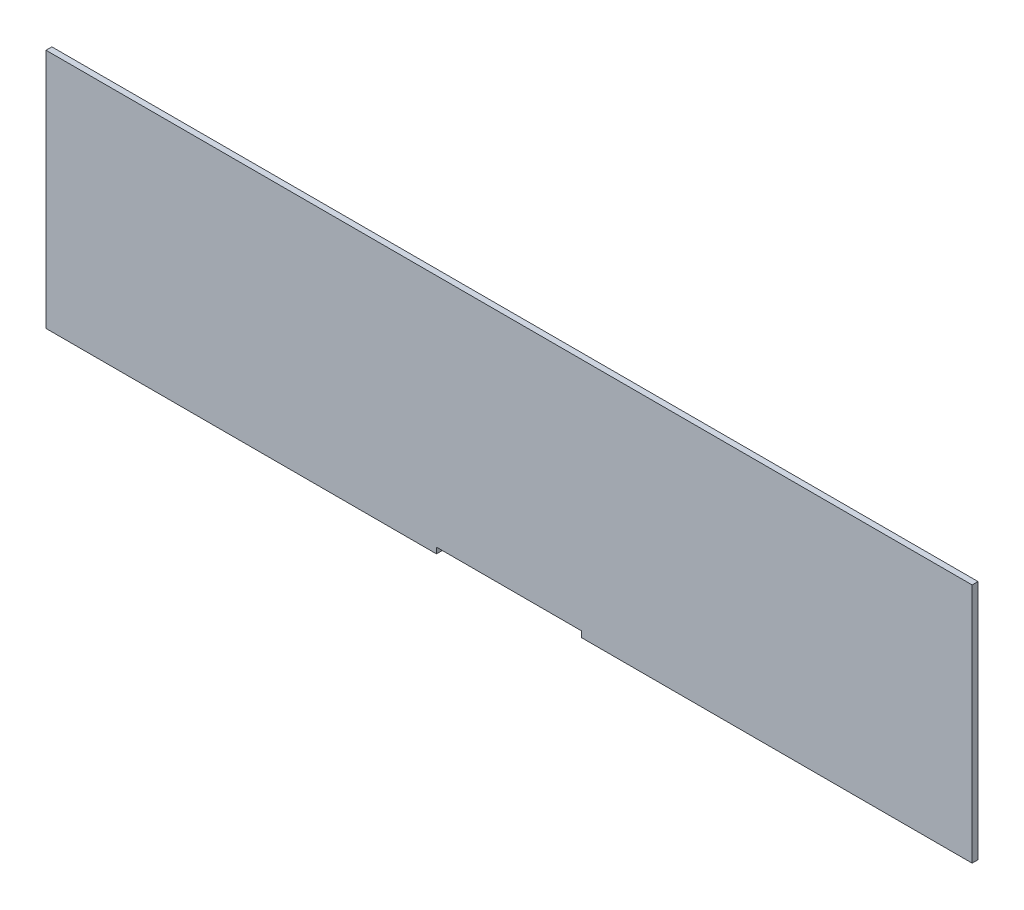
SolidWorks part; units mm, degrees
ref_plane "Front Plane" through (0, 0, 0) normal (0, 0, 1) x (1, 0, 0)
ref_plane "Top Plane" through (0, 0, 0) normal (0, 1, 0) x (1, 0, 0)
ref_plane "Right Plane" through (0, 0, 0) normal (1, 0, 0) x (0, 0, -1)
sketch "Sketch1" plane through (0, 0, 0) normal (0, 0, 1) x (1, 0, 0)
  line L0 (-37.055, 3) -> (37.055, 3)
  line L1 (-236.355, 123) -> (236.355, 123)
  line L2 (-236.355, 123) -> (-236.355, 0)
  line L3 (-236.355, 0) -> (-37.055, 0)
  line L4 (236.355, 123) -> (236.355, 0)
  line L5 (-37.055, 3) -> (-37.055, 0)
  line L6 (0, 3) -> (0, 0) construction
  line L7 (37.055, 3) -> (37.055, 0)
  line L8 (37.055, 0) -> (236.355, 0)
  point P10 (0, 0)
  dimension "D1" = 472.71
  dimension "D2" = 123
  dimension "D3" = 74.11
  dimension "D4" = 3
  dimension "D5" = 236.355
extrude "Boss-Extrude1" add sketch "Sketch1" along normal blind 3
equation "\"D5@Sketch1\"=\"D1@Sketch1\"/2"
